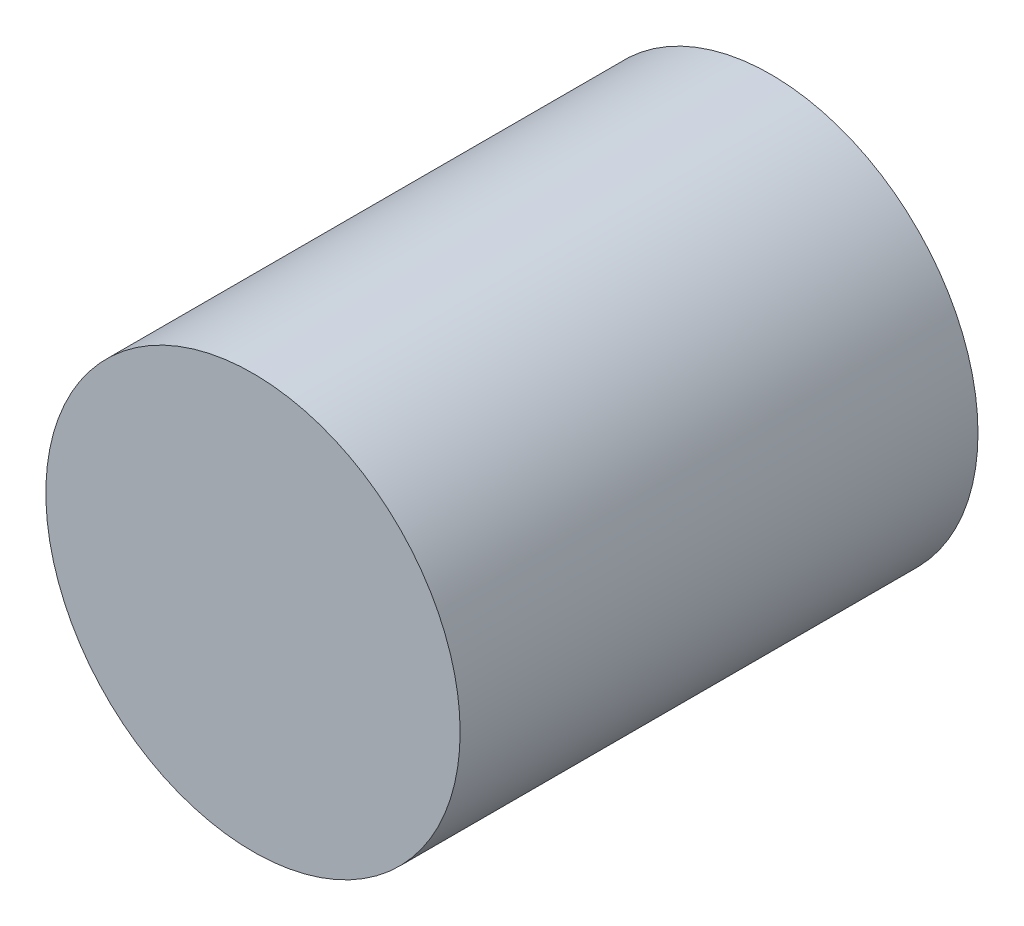
SolidWorks part; units mm, degrees
ref_plane "Alzado" through (0, 0, 0) normal (0, 0, 1) x (1, 0, 0)
ref_plane "Planta" through (0, 0, 0) normal (0, 1, 0) x (1, 0, 0)
ref_plane "Vista lateral" through (0, 0, 0) normal (1, 0, 0) x (0, 0, -1)
sketch "Croquis1" plane through (0, 0, 0) normal (0, 0, 1) x (1, 0, 0)
  circle A0 centre (0, 0) radius 10
extrude "Saliente-Extruir1" add sketch "Croquis1" along normal blind 25
